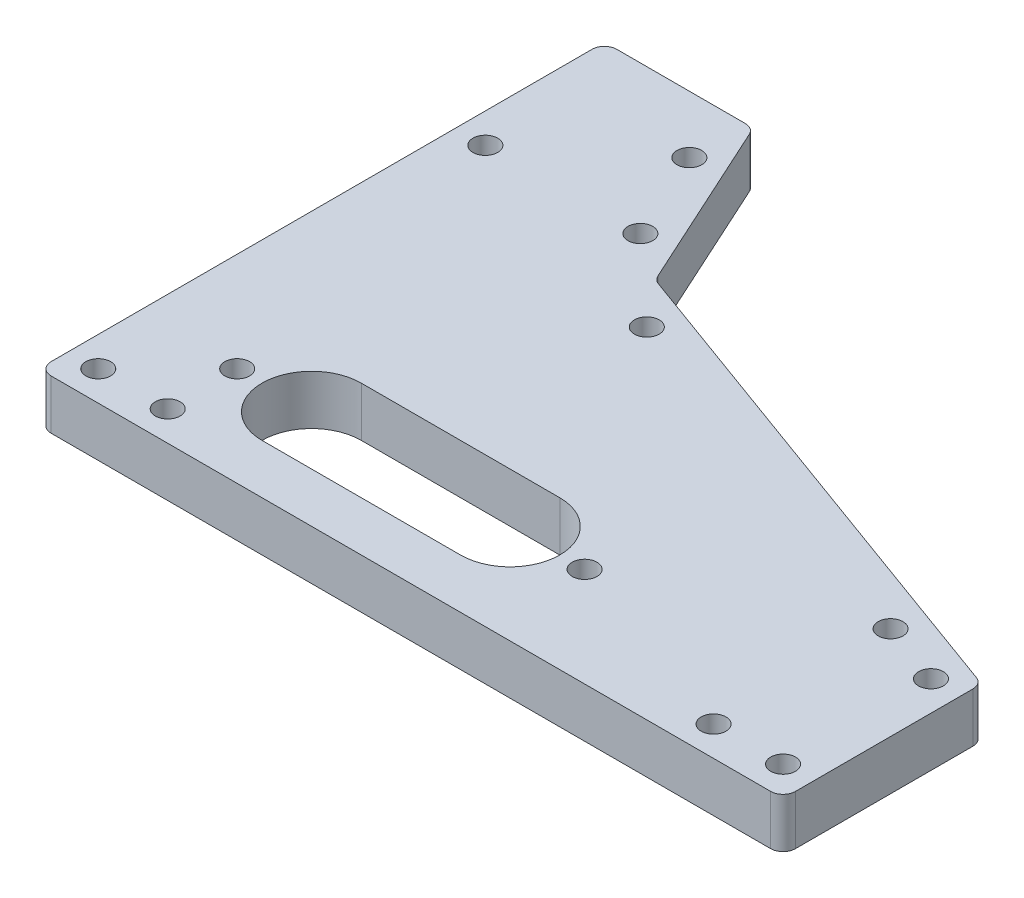
SolidWorks part; units mm, degrees
ref_plane "Front Plane" through (0, 0, 0) normal (0, 0, 1) x (1, 0, 0)
ref_plane "Top Plane" through (0, 0, 0) normal (0, 1, 0) x (1, 0, 0)
ref_plane "Right Plane" through (0, 0, 0) normal (1, 0, 0) x (0, 0, -1)
sketch "base" plane through (0, 0, 0) normal (0, 1, 0) x (1, 0, 0)
  line L0 (0, 144.7795) -> (38.1, 144.7795)
  line L1 (38.1, 144.7795) -> (59.2249, 98.5802)
  line L2 (59.2249, 98.5802) -> (190.5, 50.8)
  line L3 (190.5, 50.8) -> (190.5, 0)
  line L4 (190.5, 0) -> (0, 0)
  line L5 (0, 0) -> (0, 144.7795)
  line L6 (166.6318, 51.3783) -> (190.5, 42.691) construction
  line L7 (68.5528, 87.0761) -> (71.159, 94.2366) construction
  line L8 (38.1, 144.7795) -> (0, 127.3581) construction
  line L9 (36.4513, 130.061) -> (53.6214, 92.5107) construction
  line L10 (53.6214, 92.5107) -> (166.6318, 51.3783) construction
  line L11 (47.0138, 106.9613) -> (53.9437, 110.13) construction
  line L12 (182.88, 7.62) -> (7.62, 7.62) construction
  line L13 (95.25, 25.4) -> (44.45, 25.4) construction
  line L14 (95.25, 12.7) -> (44.45, 12.7)
  line L15 (95.25, 38.1) -> (44.45, 38.1)
  line L17 (0, 144.7795) -> (25.4, 144.7795) construction
  line L18 (0, 144.7795) -> (0, 119.3795) construction
  line L19 (0, 119.3795) -> (25.4, 119.3795) construction
  line L20 (25.4, 144.7795) -> (25.4, 119.3795) construction
  circle A0 centre (166.6318, 51.3783) radius 3.175
  circle A2 centre (36.4513, 130.061) radius 3.175
  circle A3 centre (182.88, 45.4644) radius 3.175
  circle A4 centre (68.5528, 87.0761) radius 3.175
  circle A5 centre (47.0138, 106.9613) radius 3.175
  circle A6 centre (182.88, 7.62) radius 3.175
  circle A7 centre (7.62, 7.62) radius 3.175
  circle A8 centre (7.62, 106.6795) radius 3.175
  circle A9 centre (25.4, 7.62) radius 3.175
  circle A10 centre (165.1, 7.62) radius 3.175
  arc A11 (95.25, 12.7) -> (95.25, 38.1) centre (95.25, 25.4) ccw
  arc A12 (44.45, 38.1) -> (44.45, 12.7) centre (44.45, 25.4) ccw
  circle A13 centre (25.4, 25.4) radius 3.175
  circle A14 centre (114.3, 25.4) radius 3.175
  point P32 (69.85, 25.4)
  dimension "D7" = 6.35
  dimension "D10" = 6.35
  dimension "D12" = 6.35
  dimension "D11" = 6.35
  dimension "D17" = 6.35
  dimension "D19" = 6.35
  dimension "D22" = 7.62
  dimension "D23" = 6.35
  dimension "D25" = 6.35
  dimension "D28" = 6.35
  dimension "D31" = 6.35
  dimension "D36" = 6.35
  dimension "D39" = 19.05
  dimension "D40" = 6.35
  dimension "D44" = 144.7795
  dimension "D1" = 139.7
  dimension "D2" = 50.8
  dimension "D3" = 110
  dimension "D4" = 38.1
  dimension "D5" = 50.8
  dimension "D6" = 190.5
  dimension "D8" = 7.62
  dimension "D9" = 25.4
  dimension "D13" = 7.62
  dimension "D14" = 12.7
  dimension "D15" = 7.62
  dimension "D16" = 12.7
  dimension "D18" = 12.7
  dimension "D20" = 7.62
  dimension "D21" = 7.62
  dimension "D24" = 7.62
  dimension "D26" = 7.62
  dimension "D27" = 38.1
  dimension "D29" = 25.4
  dimension "D30" = 25.4
  dimension "D32" = 50.8
  dimension "D33" = 25.4
  dimension "D34" = 25.4
  dimension "D35" = 19.05
  dimension "D37" = 25.4
  dimension "D38" = 25.4
  dimension "D41" = 25.4
  dimension "D42" = 25.4
  dimension "D43" = 25.4
extrude "Boss-Extrude1" add sketch "base" along normal blind 12.7
fillet "router_fillet" radius 3.175 6 edges at (0, 6.35, 0) (190.5, 6.35, 0) (190.5, 6.35, -50.8) (59.2249, 6.35, -98.5802) (38.1, 6.35, -144.7795) (0, 6.35, -144.7795)
